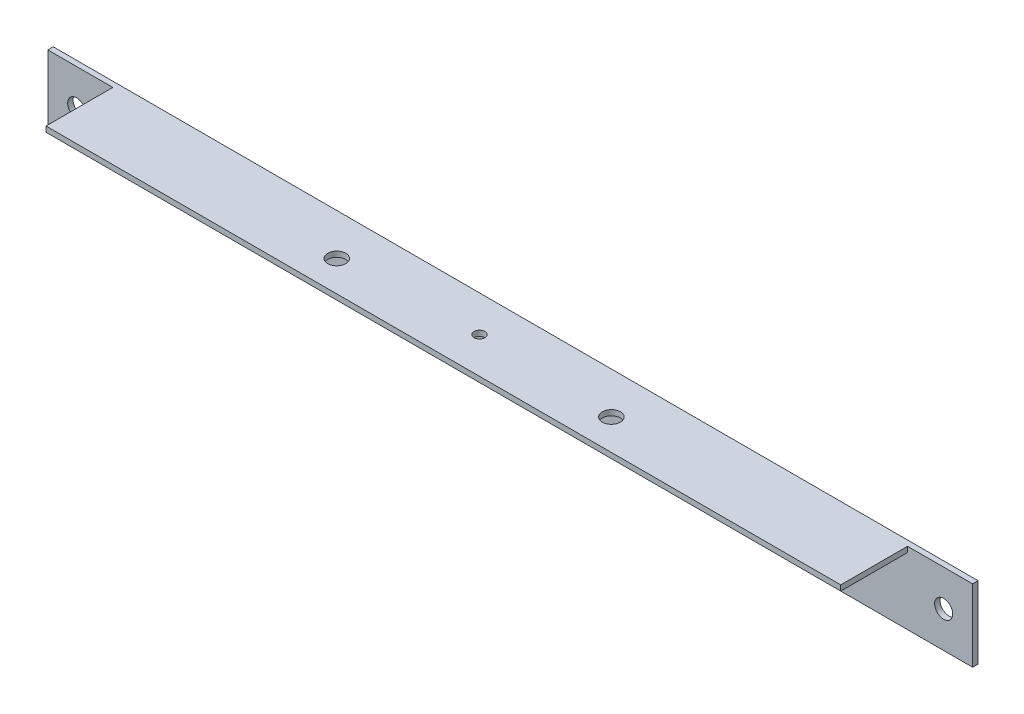
SolidWorks part; units mm, degrees
material "3.0205 (EN-AW 1200)"
ref_plane "Plan de face" through (0, 0, 0) normal (0, 0, 1) x (1, 0, 0)
ref_plane "Plan de dessus" through (0, 0, 0) normal (0, 1, 0) x (1, 0, 0)
ref_plane "Plan de droite" through (0, 0, 0) normal (1, 0, 0) x (0, 0, -1)
sketch "Esquisse1" plane through (0, 0, 0) normal (1, 0, 0) x (0, 0, -1)
  line L0 (-20, 0) -> (0, 0)
  line L1 (0, 0) -> (0, -20)
  dimension "D1" = 20
  dimension "D2" = 20
extrude "Extru.-Mince1" add sketch "Esquisse1" along normal mid plane 256 thin
sketch "Esquisse2" plane through (0, 0, 1.5) normal (0, 0, 1) x (1, 0, 0)
  line L0 (0, -20) -> (0, -1.5) construction
  line L1 (128, -20) -> (-128, -20) construction
  line L2 (128, -1.5) -> (-128, -1.5) construction
  circle A0 centre (-120, -10) radius 2.5
  circle A1 centre (120, -10) radius 2.5
  dimension "D1" = 240
  dimension "D2" = 10
  dimension "D3" = 5
extrude "Enlèv. mat.-Extru.1" cut sketch "Esquisse2" against normal blind 10
sketch "Esquisse3" plane through (0, -1.5, 0) normal (0, -1, 0) x (1, 0, 0)
  line L0 (128, 1.5) -> (-128, 1.5) construction
  line L1 (-128, 20) -> (-110, 20)
  line L2 (-128, 20) -> (-128, 1.5)
  line L3 (-128, 1.5) -> (-110, 1.5)
  line L4 (-110, 20) -> (-110, 1.5)
  line L5 (0, 0) -> (0, 20) construction
  line L6 (128, 20) -> (-128, 20) construction
  line L7 (110, 20) -> (110, 1.5)
  line L8 (128, 1.5) -> (110, 1.5)
  line L9 (128, 20) -> (128, 1.5)
  line L10 (128, 20) -> (110, 20)
  circle A0 centre (-38, 11.5) radius 2.5
  circle A1 centre (38, 11.5) radius 2.5
  dimension "D2" = 76
  dimension "D3" = 10
  dimension "D4" = 5
  dimension "D1" = 220
extrude "Enlèv. mat.-Extru.2" cut sketch "Esquisse3" against normal blind 10
sketch "Esquisse4" plane through (0, 0, 0) normal (0, 1, 0) x (1, 0, 0)
  line L0 (128, 0) -> (-128, 0) construction
  circle A0 centre (0, -10) radius 1.5
  point P4 (0, 0)
  dimension "D1" = 10
  dimension "D2" = 3
extrude "Enlèv. mat.-Extru.3" cut sketch "Esquisse4" against normal blind 5
sketch "Esquisse5" plane through (0, 0, 0) normal (0, 0, -1) x (-1, 0, 0)
  line L0 (0, 11) -> (0, -11) construction
  line L1 (-128, 0) -> (128, 0) construction
  circle A0 centre (-20, -10) radius 1.5
  circle A1 centre (20, -10) radius 1.5
  dimension "D1" = 40
  dimension "D3" = 3
  dimension "D2" = 10
extrude "Enlèv. mat.-Extru.4" cut sketch "Esquisse5" against normal blind 5
